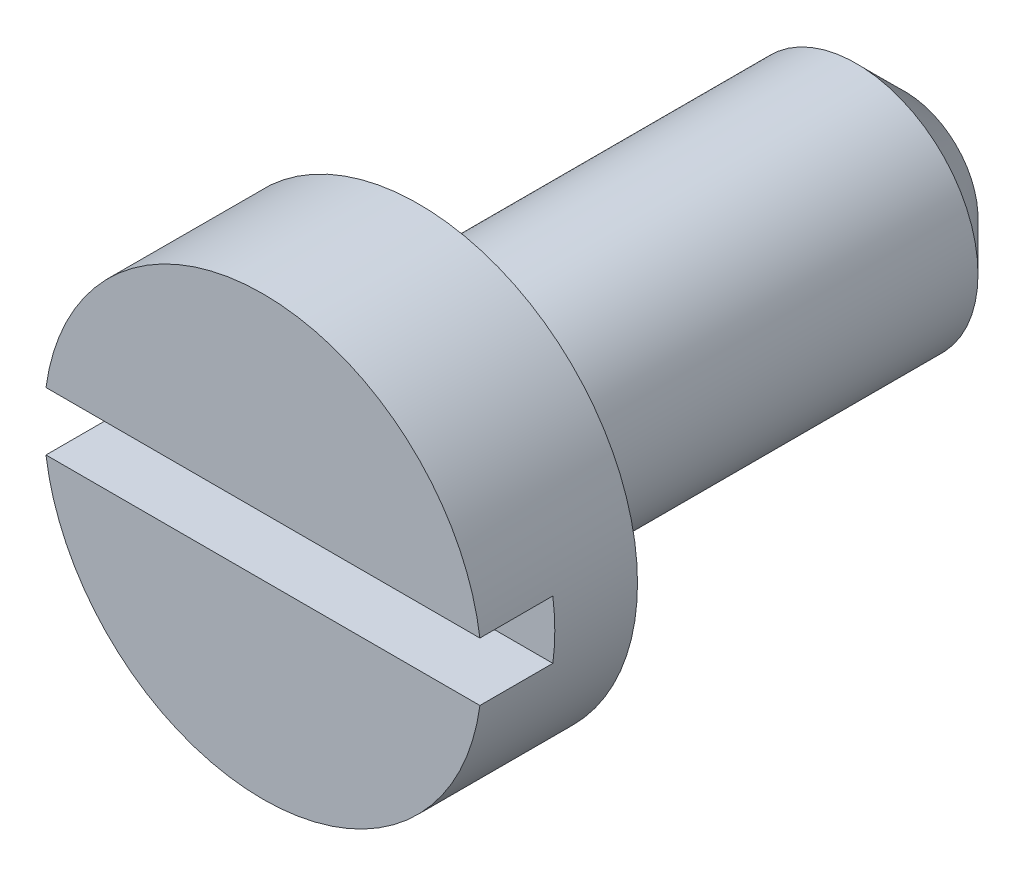
SolidWorks part; units mm, degrees
ref_plane "Спереди" through (0, 0, 0) normal (0, 0, 1) x (1, 0, 0)
ref_plane "Сверху" through (0, 0, 0) normal (0, 1, 0) x (1, 0, 0)
ref_plane "Справа" through (0, 0, 0) normal (1, 0, 0) x (0, 0, -1)
sketch "Эскиз12" plane through (0, 0, 0) normal (0, 0, 1) x (1, 0, 0)
  circle A0 centre (0, 0) radius 2.25
extrude "Вытянуть3" add sketch "Эскиз12" along normal blind 1.6
sketch "Эскиз13" plane through (0, 0, 0) normal (0, 0, -1) x (-1, 0, 0)
  circle A0 centre (0, 0) radius 1.25
extrude "Вытянуть4" add sketch "Эскиз13" along normal blind 5
sketch "Эскиз14" plane through (0, 0, 1.6) normal (0, 0, 1) x (1, 0, 0)
  line L0 (-2.25, 0) -> (2.25, 0) construction
  circle A0 centre (0, 0) radius 2.25 construction
sketch "Эскиз20" plane through (0, 0, 1.6) normal (0, 0, 1) x (1, 0, 0)
  line L0 (-2.25, 0) -> (2.25, 0) construction
  line L1 (-2.6691, 0.3) -> (2.7076, 0.3)
  line L2 (-2.6691, 0.3) -> (-2.6691, -0.3)
  line L3 (-2.6691, -0.3) -> (2.7076, -0.3)
  line L4 (2.7076, 0.3) -> (2.7076, -0.3)
  dimension "D1" = 0.3
  dimension "D2" = 0.3
extrude "Вырез-Вытянуть8" cut sketch "Эскиз20" against normal blind 0.75
chamfer "Фаска1" distance 0.5 angle 45 1 edges at (-1.25, 0, -5)
